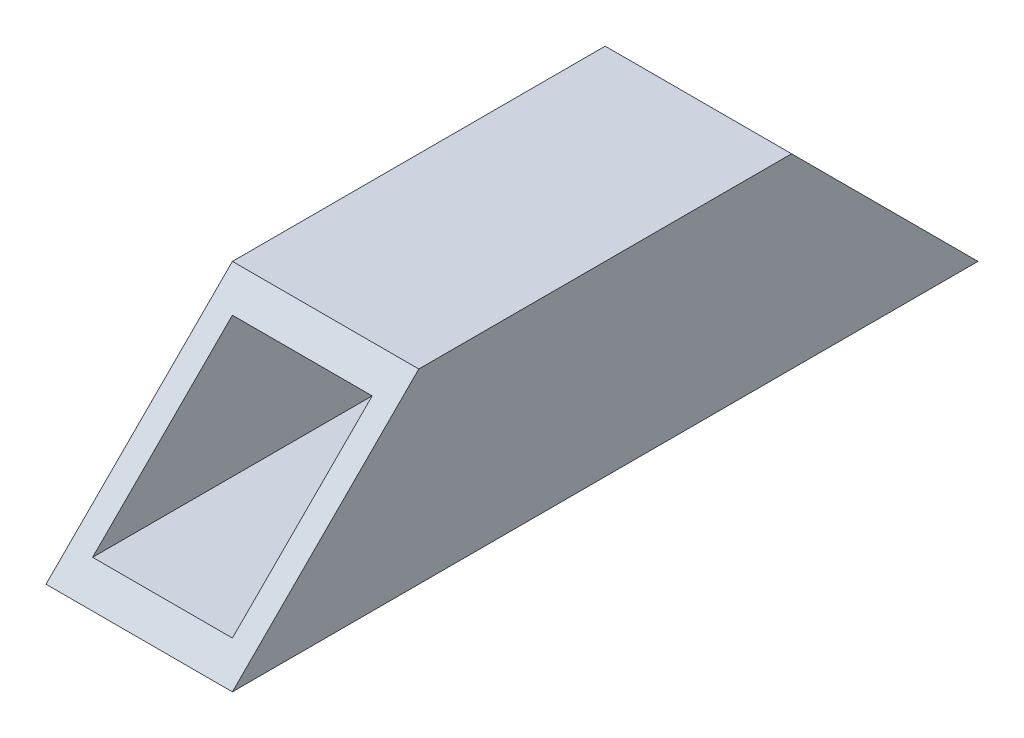
SolidWorks part; units mm, degrees
ref_plane "Front Plane" through (0, 0, 0) normal (0, 0, 1) x (1, 0, 0)
ref_plane "Top Plane" through (0, 0, 0) normal (0, 1, 0) x (1, 0, 0)
ref_plane "Right Plane" through (0, 0, 0) normal (1, 0, 0) x (0, 0, -1)
sketch "Sketch1" plane through (0, 0, 0) normal (0, 0, 1) x (1, 0, 0)
  line L1 (-12.7, -12.7) -> (12.7, -12.7)
  line L2 (-12.7, -12.7) -> (-12.7, 12.7)
  line L3 (-12.7, 12.7) -> (12.7, 12.7)
  line L4 (12.7, -12.7) -> (12.7, 12.7)
  line L5 (-12.7, -12.7) -> (12.7, 12.7) construction
  line L6 (-12.7, 12.7) -> (12.7, -12.7) construction
  line L7 (-9.525, -9.525) -> (9.525, -9.525)
  line L8 (-9.525, -9.525) -> (-9.525, 9.525)
  line L9 (-9.525, 9.525) -> (9.525, 9.525)
  line L10 (9.525, -9.525) -> (9.525, 9.525)
  line L11 (-9.525, -9.525) -> (9.525, 9.525) construction
  line L12 (-9.525, 9.525) -> (9.525, -9.525) construction
  point P0 (0, 0)
  point P6 (0, 0)
  dimension "D1" = 25.4
  dimension "D2" = 25.4
  dimension "D3" = 3.175
extrude "Boss-Extrude1" add sketch "Sketch1" along normal blind 101.6
sketch "Sketch2" plane through (12.7, 0, 0) normal (1, 0, 0) x (0, 0, -1)
  line L4 (0, -12.7) -> (0, 12.7)
  line L5 (0, 12.7) -> (-101.6, 12.7)
  line L6 (-101.6, 12.7) -> (-101.6, -12.7)
  line L7 (-101.6, -12.7) -> (0, -12.7)
  line L8 (0, -12.7) -> (0, 12.7)
  line L9 (0, 12.7) -> (-101.6, 12.7)
  line L10 (-101.6, 12.7) -> (-101.6, -12.7)
  line L11 (-101.6, -12.7) -> (0, -12.7)
  line L12 (-101.6, -12.7) -> (-76.2, 12.7)
  line L13 (0, -12.7) -> (-25.4, 12.7)
  line M7 (0, -12.7) -> (0, 12.7)
  line M8 (0, 12.7) -> (-101.6, 12.7)
  line M9 (-101.6, 12.7) -> (-101.6, -12.7)
  dimension "D2" = 45
  dimension "D3" = 45
  dimension "D1" = 0
extrude "Cut-Extrude1" cut sketch "Sketch2" against normal up to surface (25.4 mm away) contours L12 L9 M9 | L13 M7 M8 up to face at (-12.7, 0, 50.8)
